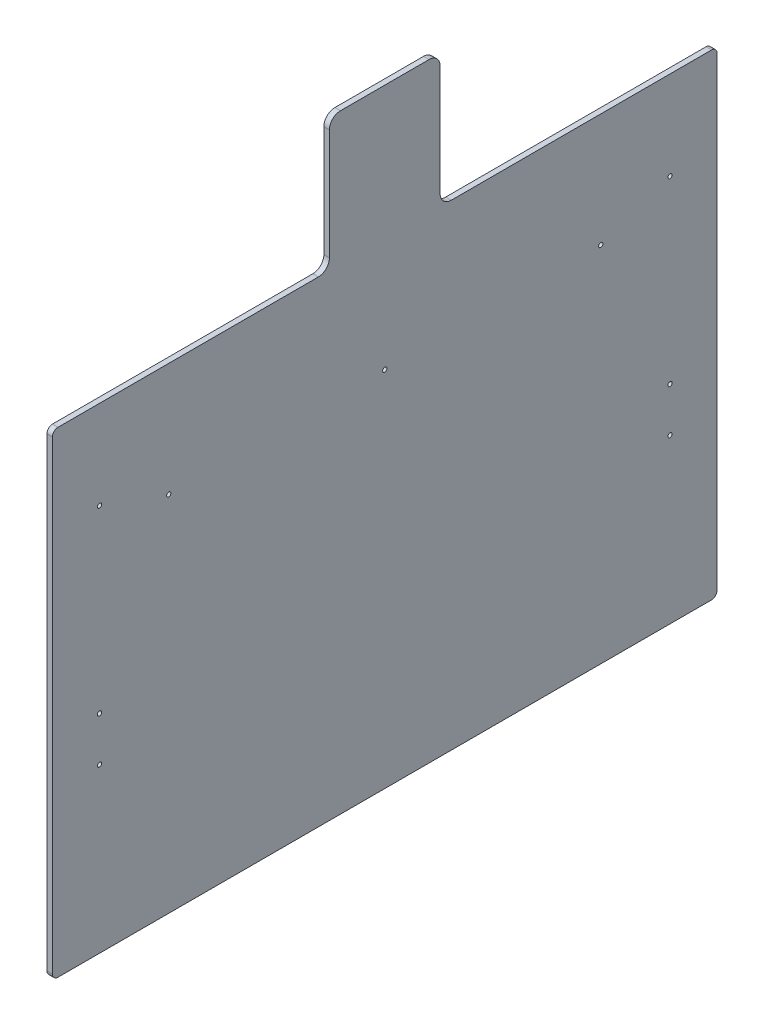
SolidWorks part; units mm, degrees
material "PE High Density"
ref_plane "Front Plane" through (0, 0, 0) normal (0, 0, 1) x (1, 0, 0)
ref_plane "Top Plane" through (0, 0, 0) normal (0, 1, 0) x (1, 0, 0)
ref_plane "Right Plane" through (0, 0, 0) normal (1, 0, 0) x (0, 0, -1)
sketch "Sketch1" plane through (0, 0, 0) normal (1, 0, 0) x (0, 0, -1)
  line L0 (457.2, 546.1) -> (755.65, 546.1)
  line L1 (6.35, 0) -> (755.65, 0)
  line L2 (0, 6.35) -> (0, 539.75)
  line L3 (6.35, 546.1) -> (304.8, 546.1)
  line L4 (762, 6.35) -> (762, 539.75)
  line L6 (317.5, 558.8) -> (317.5, 685.8)
  line L7 (330.2, 698.5) -> (431.8, 698.5)
  line L8 (444.5, 558.8) -> (444.5, 685.8)
  arc A0 (6.35, 0) -> (0, 6.35) centre (6.35, 6.35) cw
  arc A1 (755.65, 0) -> (762, 6.35) centre (755.65, 6.35) ccw
  arc A2 (755.65, 546.1) -> (762, 539.75) centre (755.65, 539.75) cw
  arc A3 (0, 539.75) -> (6.35, 546.1) centre (6.35, 539.75) cw
  circle A4 centre (53.975, 444.5) radius 2.4575
  circle A5 centre (708.025, 444.5) radius 2.4575
  circle A6 centre (708.025, 238.125) radius 2.4575
  circle A8 centre (53.975, 238.125) radius 2.4574
  circle A9 centre (53.975, 187.325) radius 2.4574
  circle A10 centre (708.025, 187.325) radius 2.4575
  arc A11 (304.8, 546.1) -> (317.5, 558.8) centre (304.8, 558.8) ccw
  arc A12 (457.2, 546.1) -> (444.5, 558.8) centre (457.2, 558.8) cw
  arc A13 (431.8, 698.5) -> (444.5, 685.8) centre (431.8, 685.8) cw
  arc A14 (317.5, 685.8) -> (330.2, 698.5) centre (330.2, 685.8) cw
  point P7 (0, 0)
  point P12 (762, 546.1)
  point P15 (0, 546.1)
  point P34 (317.5, 546.1)
  point P39 (444.5, 698.5)
  point P42 (317.5, 698.5)
  dimension "D3" = 6.35
  dimension "D6" = 4.9149
  dimension "D11" = 53.975
  dimension "D13" = 50.8
  dimension "D17" = 12.7
  dimension "D1" = 546.1
  dimension "D2" = 762
  dimension "D4" = 654.05
  dimension "D5" = 101.6
  dimension "D9" = 53.975
  dimension "D10" = 206.375
  dimension "D12" = 50.8
  dimension "D14" = 127
  dimension "D15" = 317.5
  dimension "D16" = 152.4
  dimension "D7" = 2
  dimension "D8" = 2
extrude "Boss-Extrude1" add sketch "Sketch1" along normal blind 6.35
sketch "Sketch3" plane through (6.35, 0, 0) normal (1, 0, 0) x (0, 0, -1)
  line L13 (304.8, 546.1) -> (6.35, 546.1) construction
  line L14 (0, 539.75) -> (0, 6.35) construction
  circle A2 centre (133.35, 415.925) radius 2.4575
  circle A3 centre (381, 415.925) radius 2.4574
  circle A4 centre (628.65, 415.925) radius 2.4575
  dimension "D2" = 130.175
  dimension "D12" = 4.9149
  dimension "D6" = 133.35
  dimension "D4" = 247.65
  dimension "D5" = 247.65
extrude "Cut-Extrude2" cut sketch "Sketch3" against normal through all
